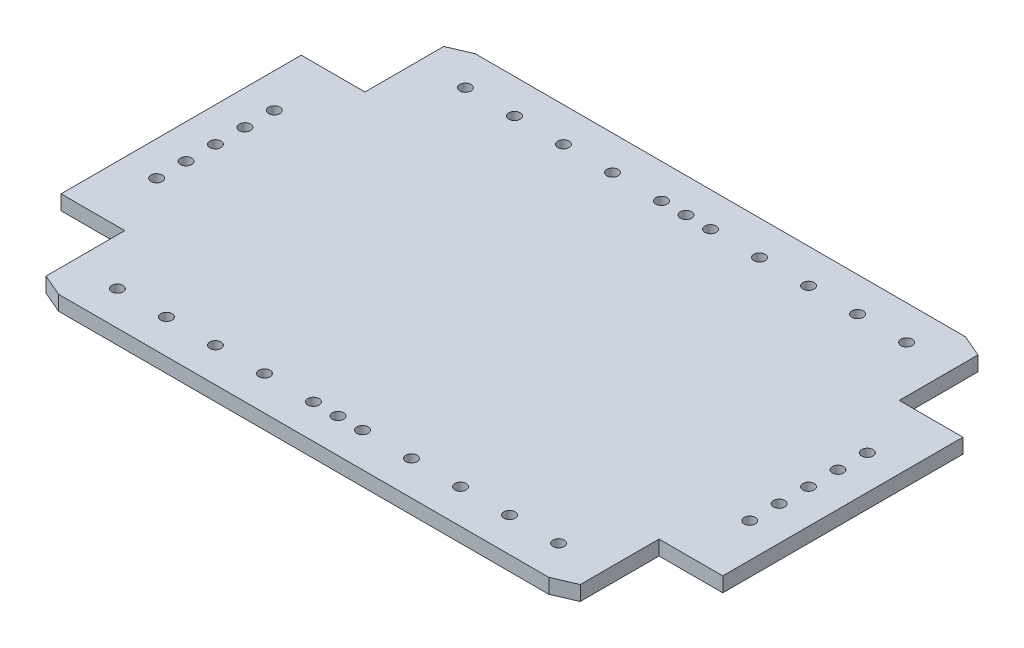
SolidWorks part; units mm, degrees
ref_plane "Plan de face" through (0, 0, 0) normal (0, 0, 1) x (1, 0, 0)
ref_plane "Plan de dessus" through (0, 0, 0) normal (0, 1, 0) x (1, 0, 0)
ref_plane "Plan de droite" through (0, 0, 0) normal (1, 0, 0) x (0, 0, -1)
sketch "Esquisse1" plane through (0, 0, 0) normal (0, 1, 0) x (1, 0, 0)
  line L0 (0, 0) -> (135, 0) construction
  line L1 (0, 0) -> (-135, 0) construction
  line L2 (-135, 0) -> (-135, -70)
  line L3 (-135, -85) -> (135, -85) construction
  line L4 (135, 0) -> (135, 70)
  line L5 (0, 85) -> (0, -85) construction
  line L6 (135, 85) -> (-135, 85) construction
  line L24 (0, -85) -> (-100, -85)
  line L26 (0, -85) -> (100, -85)
  line L28 (135, 0) -> (135, -70)
  line L31 (0, 85) -> (-100, 85)
  line L32 (0, 85) -> (100, 85)
  line L34 (-135, 0) -> (-135, 70)
  line L35 (-135, -70) -> (-100, -85)
  line L37 (-135, 70) -> (-100, 85)
  line L38 (100, 85) -> (135, 70)
  line L39 (100, -85) -> (135, -70)
  line L40 (-135, 70) -> (-100, 70) construction
  line L41 (-100, 70) -> (-100, 85) construction
  dimension "D1" = 38.0789
  dimension "D2" = 200
  dimension "D3" = 140
  dimension "D4" = 200
  dimension "D5" = 140
  dimension "D6" = 35
  dimension "D7" = 15
  dimension "D8" = 170
  dimension "D9" = 270
extrude "Boss.-Extru.1" add sketch "Esquisse1" along normal blind 6
sketch "Esquisse15" plane through (0, 6, 0) normal (0, 1, 0) x (1, 0, 0)
  line L0 (-135, 60) -> (-135, 70)
  line L1 (-135, 60) -> (-120, 60) construction
  line L2 (-135, -60) -> (-120, -60) construction
  line L4 (-135, -60) -> (-135, -70)
  line L5 (-100, 85) -> (-135, 70) construction
  line L6 (-135, 70) -> (-135, -70) construction
  circle A0 centre (-120, 60) radius 2.3
  circle A1 centre (-120, -60) radius 2.3
extrude "Enlèv. mat.-Extru.6" cut sketch "Esquisse15" against normal up to next contours A1 | A0
mirror "Symétrie5" about plane through (0, 0, 0) normal (1, 0, 0) of "Enlèv. mat.-Extru.6"
sketch "Esquisse17" plane through (0, 6, 0) normal (0, 1, 0) x (1, 0, 0)
  line L0 (0, -85) -> (0, -71) construction
  line L1 (-100, -85) -> (100, -85) construction
  line L2 (-148.5, 0) -> (148.5, 0) construction
  line L4 (0, 85) -> (0, 71) construction
  circle A0 centre (0, -71) radius 2.3
  circle A3 centre (10, -71) radius 2.3
  circle A5 centre (-10, -71) radius 2.3
  circle A6 centre (30, -71) radius 2.3
  circle A7 centre (50, -71) radius 2.3
  circle A9 centre (90, -71) radius 2.3
  circle A11 centre (-50, -71) radius 2.3
  circle A13 centre (-90, -71) radius 2.3
  circle A14 centre (-90, 71) radius 2.3
  circle A16 centre (-50, 71) radius 2.3
  circle A17 centre (-30, 71) radius 2.3
  circle A18 centre (90, 71) radius 2.3
  circle A20 centre (50, 71) radius 2.3
  circle A21 centre (30, 71) radius 2.3
  circle A22 centre (-10, 71) radius 2.3
  circle A23 centre (10, 71) radius 2.3
  circle A24 centre (0, 71) radius 2.3
  circle A25 centre (-70, -71) radius 2.3 [skipped]
  circle A26 centre (70, -71) radius 2.3 [skipped]
  circle A27 centre (-70, -71) radius 2.3
  circle A28 centre (-30, -71) radius 2.3
  circle A29 centre (70, -71) radius 2.3
  circle A30 centre (70, 71) radius 2.3
  circle A31 centre (-70, 71) radius 2.3
  circle A32 centre (-30, -71) radius 2.3 [skipped]
  dimension "D1" = 2
  dimension "D3" = 2
  dimension "D2" = 5
  dimension "D4" = 5
  dimension "D5" = 2
  dimension "D6" = 2
  dimension "D7" = 2
  dimension "D8" = 2
extrude "Enlèv. mat.-Extru.7" cut sketch "Esquisse17" against normal up to next
sketch "Esquisse20" plane through (0, 6, 0) normal (0, 1, 0) x (1, 0, 0)
  line L0 (-120, -60) -> (-109, -60) construction
  line L1 (-109, -60) -> (-109, -81.1429)
  line L2 (-135, -70) -> (-100, -85) construction
  line L3 (-109, -60) -> (-109, -49)
  line L4 (-109, -49) -> (-135, -49)
  line L5 (-135, 70) -> (-135, -70) construction
  line L6 (-135, -49) -> (-135, -70.5714)
  line L7 (-135, -70.5714) -> (-109, -81.1429)
extrude "Enlèv. mat.-Extru.10" cut sketch "Esquisse20" against normal up to next
mirror "Symétrie7" about plane through (0, 0, 0) normal (1, 0, 0) of "Enlèv. mat.-Extru.10"
mirror "Symétrie8" about plane through (0, 0, 0) normal (0, 0, 1) of "Symétrie7", "Enlèv. mat.-Extru.10"
sketch "Esquisse21" plane through (0, 6, 0) normal (0, 1, 0) x (1, 0, 0)
  line L0 (-135, 0) -> (-121, 0) construction
  line L1 (-135, 49) -> (-135, -49) construction
  line L2 (0, -93.5) -> (0, 93.5) construction
  line L4 (135, 0) -> (121, 0) construction
  circle A16 centre (-121, 24) radius 2.3
  circle A17 centre (-121, 12) radius 2.3
  circle A19 centre (-121, -24) radius 2.3
  circle A20 centre (-121, -12) radius 2.3
  circle A35 centre (-121, 0) radius 2.3
  circle A36 centre (121, 0) radius 2.3
  circle A37 centre (121, -12) radius 2.3
  circle A38 centre (121, -24) radius 2.3
  circle A40 centre (121, 12) radius 2.3
  circle A41 centre (121, 24) radius 2.3
extrude "Enlèv. mat.-Extru.11" cut sketch "Esquisse21" against normal up to next
